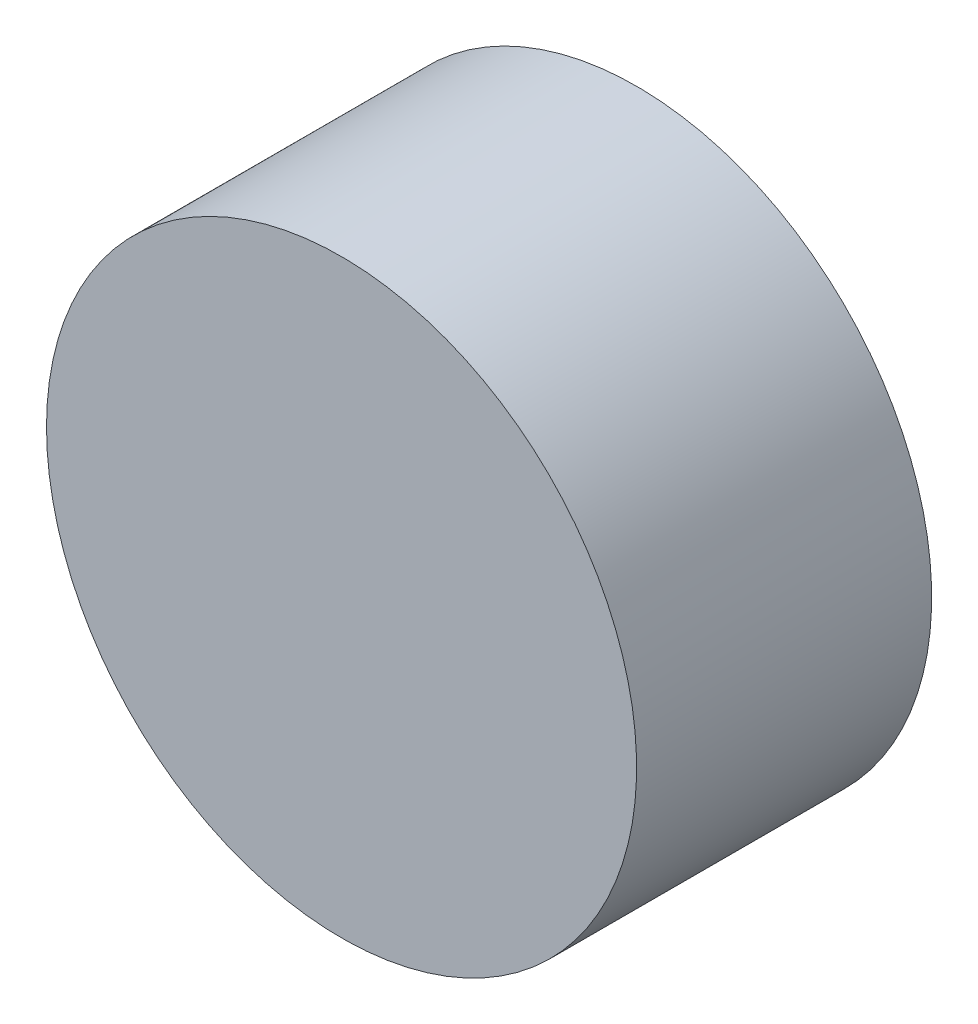
SolidWorks part; units mm, degrees
ref_plane "Front Plane" through (0, 0, 0) normal (0, 0, 1) x (1, 0, 0)
ref_plane "Top Plane" through (0, 0, 0) normal (0, 1, 0) x (1, 0, 0)
ref_plane "Right Plane" through (0, 0, 0) normal (1, 0, 0) x (0, 0, -1)
sketch "Sketch1" plane through (0, 0, 0) normal (0, 0, 1) x (1, 0, 0)
  circle A0 centre (-19.5938, 20.601) radius 76.2
  point P2 (0, 0)
extrude "Boss-Extrude1" add sketch "Sketch1" along normal blind 76.2 contours A0
